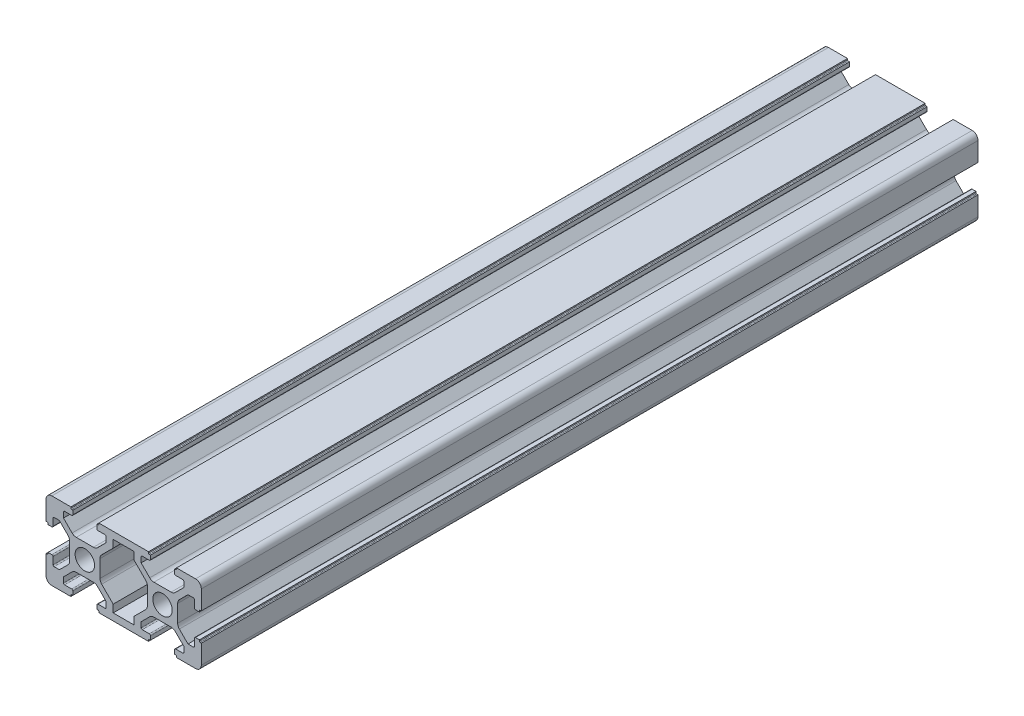
SolidWorks part; units mm, degrees
ref_plane "前视基准面" through (0, 0, 0) normal (0, 0, 1) x (1, 0, 0)
ref_plane "上视基准面" through (0, 0, 0) normal (0, 1, 0) x (1, 0, 0)
ref_plane "右视基准面" through (0, 0, 0) normal (1, 0, 0) x (0, 0, -1)
sketch "草图1" plane through (0, 0, 0) normal (0, 0, 1) x (1, 0, 0)
  line L0 (-1.9716, -6.6942) -> (-4.9322, -3.7335)
  line L1 (-5.3716, -2.6729) -> (-5.3716, 1.7645)
  line L2 (-4.9322, 2.8251) -> (-1.9716, 5.7858)
  line L3 (-0.7716, 9.5458) -> (-5.6716, 9.5458)
  line L4 (-5.6716, 9.5458) -> (-5.6716, 9.2458)
  line L5 (-5.8716, 9.0458) -> (-6.1716, 9.0458)
  line L6 (-6.1716, 9.0458) -> (-6.1716, 8.0458)
  line L7 (-5.8716, 7.7458) -> (-4.0716, 7.7458)
  line L8 (-3.7716, 7.4458) -> (-3.7716, 6.1058)
  line L9 (-3.7716, 6.1058) -> (-5.9922, 3.8851)
  line L10 (-7.0529, 3.4458) -> (-11.4903, 3.4458)
  line L11 (-12.5509, 3.8851) -> (-14.7716, 6.1058)
  line L12 (-14.7716, 6.1058) -> (-14.7716, 7.4458)
  line L13 (-14.4716, 7.7458) -> (-12.6716, 7.7458)
  line L14 (-12.3716, 8.0458) -> (-12.3716, 9.0458)
  line L15 (-12.3716, 9.0458) -> (-12.6716, 9.0458)
  line L16 (-12.8716, 9.2458) -> (-12.8716, 9.5458)
  line L17 (-12.8716, 9.5458) -> (-17.7716, 9.5458)
  line L18 (-19.2716, 8.0458) -> (-19.2716, 3.1458)
  line L19 (-19.2716, 3.1458) -> (-18.9716, 3.1458)
  line L20 (-18.7716, 2.9458) -> (-18.7716, 2.6458)
  line L21 (-18.7716, 2.6458) -> (-17.7716, 2.6458)
  line L22 (-17.4716, 2.9458) -> (-17.4716, 4.7458)
  line L23 (-17.1716, 5.0458) -> (-15.8316, 5.0458)
  line L24 (-15.8316, 5.0458) -> (-13.6109, 2.8251)
  line L25 (-13.1716, 1.7645) -> (-13.1716, -2.6729)
  line L26 (-13.6109, -3.7335) -> (-15.8316, -5.9542)
  line L27 (-15.8316, -5.9542) -> (-17.1716, -5.9542)
  line L28 (-17.4716, -5.6542) -> (-17.4716, -3.8542)
  line L29 (-17.7716, -3.5542) -> (-18.7716, -3.5542)
  line L30 (-18.7716, -3.5542) -> (-18.7716, -3.8542)
  line L31 (-18.9716, -4.0542) -> (-19.2716, -4.0542)
  line L32 (-19.2716, -4.0542) -> (-19.2716, -8.9542)
  line L33 (-17.7716, -10.4542) -> (-12.8716, -10.4542)
  line L34 (-12.8716, -10.4542) -> (-12.8716, -10.1542)
  line L35 (-12.6716, -9.9542) -> (-12.3716, -9.9542)
  line L36 (-12.3716, -9.9542) -> (-12.3716, -8.9542)
  line L37 (-12.6716, -8.6542) -> (-14.4716, -8.6542)
  line L38 (-14.7716, -8.3542) -> (-14.7716, -7.0142)
  line L39 (-14.7716, -7.0142) -> (-12.5509, -4.7935)
  line L40 (-11.4903, -4.3542) -> (-7.0529, -4.3542)
  line L41 (-5.9922, -4.7935) -> (-3.7716, -7.0142)
  line L42 (-3.7716, -7.0142) -> (-3.7716, -8.3542)
  line L43 (-4.0716, -8.6542) -> (-5.8716, -8.6542)
  line L44 (-6.1716, -8.9542) -> (-6.1716, -9.9542)
  line L45 (-6.1716, -9.9542) -> (-5.8716, -9.9542)
  line L46 (-5.6716, -10.1542) -> (-5.6716, -10.4542)
  line L47 (-5.6716, -10.4542) -> (-0.7716, -10.4542)
  line L48 (-0.7716, -10.4542) -> (7.1284, -10.4542)
  line L49 (7.1284, -10.4542) -> (7.1284, -10.1542)
  line L50 (7.3284, -9.9542) -> (7.6284, -9.9542)
  line L51 (7.6284, -9.9542) -> (7.6284, -8.9542)
  line L52 (7.3284, -8.6542) -> (5.5284, -8.6542)
  line L53 (5.2284, -8.3542) -> (5.2284, -7.0142)
  line L54 (5.2284, -7.0142) -> (7.4491, -4.7935)
  line L55 (8.5097, -4.3542) -> (12.9471, -4.3542)
  line L56 (14.0078, -4.7935) -> (16.2284, -7.0142)
  line L57 (16.2284, -7.0142) -> (16.2284, -8.3542)
  line L58 (15.9284, -8.6542) -> (14.1284, -8.6542)
  line L59 (13.8284, -8.9542) -> (13.8284, -9.9542)
  line L60 (13.8284, -9.9542) -> (14.1284, -9.9542)
  line L61 (14.3284, -10.1542) -> (14.3284, -10.4542)
  line L62 (14.3284, -10.4542) -> (19.2284, -10.4542)
  line L63 (20.7284, -8.9542) -> (20.7284, -4.0542)
  line L64 (20.7284, -4.0542) -> (20.4284, -4.0542)
  line L65 (20.2284, -3.8542) -> (20.2284, -3.5542)
  line L66 (20.2284, -3.5542) -> (19.2284, -3.5542)
  line L67 (18.9284, -3.8542) -> (18.9284, -5.6542)
  line L68 (18.6284, -5.9542) -> (17.2884, -5.9542)
  line L69 (17.2884, -5.9542) -> (15.0678, -3.7335)
  line L70 (14.6284, -2.6729) -> (14.6284, 1.7645)
  line L71 (15.0678, 2.8251) -> (17.2884, 5.0458)
  line L72 (17.2884, 5.0458) -> (18.6284, 5.0458)
  line L73 (18.9284, 4.7458) -> (18.9284, 2.9458)
  line L74 (19.2284, 2.6458) -> (20.2284, 2.6458)
  line L75 (20.2284, 2.6458) -> (20.2284, 2.9458)
  line L76 (20.4284, 3.1458) -> (20.7284, 3.1458)
  line L77 (20.7284, 3.1458) -> (20.7284, 8.0458)
  line L78 (19.2284, 9.5458) -> (14.3284, 9.5458)
  line L79 (14.3284, 9.5458) -> (14.3284, 9.2458)
  line L80 (14.1284, 9.0458) -> (13.8284, 9.0458)
  line L81 (13.8284, 9.0458) -> (13.8284, 8.0458)
  line L82 (14.1284, 7.7458) -> (15.9284, 7.7458)
  line L83 (16.2284, 7.4458) -> (16.2284, 6.1058)
  line L84 (16.2284, 6.1058) -> (14.0078, 3.8851)
  line L85 (12.9471, 3.4458) -> (8.5097, 3.4458)
  line L86 (7.4491, 3.8851) -> (5.2284, 6.1058)
  line L87 (5.2284, 6.1058) -> (5.2284, 7.4458)
  line L88 (5.5284, 7.7458) -> (7.3284, 7.7458)
  line L89 (7.6284, 8.0458) -> (7.6284, 9.0458)
  line L90 (7.6284, 9.0458) -> (7.3284, 9.0458)
  line L91 (7.1284, 9.2458) -> (7.1284, 9.5458)
  line L92 (7.1284, 9.5458) -> (2.2284, 9.5458)
  line L93 (3.4284, 5.7858) -> (6.3891, 2.8251)
  line L94 (6.8284, 1.7645) -> (6.8284, -2.6729)
  line L95 (6.3891, -3.7335) -> (3.4284, -6.6942)
  line L96 (-0.7716, 9.5458) -> (2.2284, 9.5458)
  line L99 (-1.9716, 7.7458) -> (3.4284, 7.7458)
  line L100 (3.4284, 7.7458) -> (3.4284, 5.7858)
  line L101 (-1.9716, 7.7458) -> (-1.9716, 5.7858)
  line L102 (-1.9716, -8.6542) -> (3.4284, -8.6542)
  line L103 (3.4284, -8.6542) -> (3.4284, -6.6942)
  line L104 (-1.9716, -8.6542) -> (-1.9716, -6.6942)
  arc A1 (-5.3716, -2.6729) -> (-4.9322, -3.7335) centre (-3.8716, -2.6729) ccw
  arc A2 (-4.9322, 2.8251) -> (-5.3716, 1.7645) centre (-3.8716, 1.7645) ccw
  arc A3 (-5.8716, 9.0458) -> (-5.6716, 9.2458) centre (-5.8716, 9.2458) ccw
  arc A4 (-6.1716, 8.0458) -> (-5.8716, 7.7458) centre (-5.8716, 8.0458) ccw
  arc A5 (-3.7716, 7.4458) -> (-4.0716, 7.7458) centre (-4.0716, 7.4458) ccw
  arc A6 (-7.0529, 3.4458) -> (-5.9922, 3.8851) centre (-7.0529, 4.9458) ccw
  arc A7 (-12.5509, 3.8851) -> (-11.4903, 3.4458) centre (-11.4903, 4.9458) ccw
  arc A8 (-14.4716, 7.7458) -> (-14.7716, 7.4458) centre (-14.4716, 7.4458) ccw
  arc A9 (-12.6716, 7.7458) -> (-12.3716, 8.0458) centre (-12.6716, 8.0458) ccw
  arc A10 (-12.8716, 9.2458) -> (-12.6716, 9.0458) centre (-12.6716, 9.2458) ccw
  arc A11 (-17.7716, 9.5458) -> (-19.2716, 8.0458) centre (-17.7716, 8.0458) ccw
  arc A12 (-18.7716, 2.9458) -> (-18.9716, 3.1458) centre (-18.9716, 2.9458) ccw
  arc A13 (-17.7716, 2.6458) -> (-17.4716, 2.9458) centre (-17.7716, 2.9458) ccw
  arc A14 (-17.1716, 5.0458) -> (-17.4716, 4.7458) centre (-17.1716, 4.7458) ccw
  arc A15 (-13.1716, 1.7645) -> (-13.6109, 2.8251) centre (-14.6716, 1.7645) ccw
  arc A16 (-13.6109, -3.7335) -> (-13.1716, -2.6729) centre (-14.6716, -2.6729) ccw
  arc A17 (-17.4716, -5.6542) -> (-17.1716, -5.9542) centre (-17.1716, -5.6542) ccw
  arc A18 (-17.4716, -3.8542) -> (-17.7716, -3.5542) centre (-17.7716, -3.8542) ccw
  arc A19 (-18.9716, -4.0542) -> (-18.7716, -3.8542) centre (-18.9716, -3.8542) ccw
  arc A20 (-19.2716, -8.9542) -> (-17.7716, -10.4542) centre (-17.7716, -8.9542) ccw
  arc A21 (-12.6716, -9.9542) -> (-12.8716, -10.1542) centre (-12.6716, -10.1542) ccw
  arc A22 (-12.3716, -8.9542) -> (-12.6716, -8.6542) centre (-12.6716, -8.9542) ccw
  arc A23 (-14.7716, -8.3542) -> (-14.4716, -8.6542) centre (-14.4716, -8.3542) ccw
  arc A24 (-11.4903, -4.3542) -> (-12.5509, -4.7935) centre (-11.4903, -5.8542) ccw
  arc A25 (-5.9922, -4.7935) -> (-7.0529, -4.3542) centre (-7.0529, -5.8542) ccw
  arc A26 (-4.0716, -8.6542) -> (-3.7716, -8.3542) centre (-4.0716, -8.3542) ccw
  arc A27 (-5.8716, -8.6542) -> (-6.1716, -8.9542) centre (-5.8716, -8.9542) ccw
  arc A28 (-5.6716, -10.1542) -> (-5.8716, -9.9542) centre (-5.8716, -10.1542) ccw
  arc A29 (7.3284, -9.9542) -> (7.1284, -10.1542) centre (7.3284, -10.1542) ccw
  arc A30 (7.6284, -8.9542) -> (7.3284, -8.6542) centre (7.3284, -8.9542) ccw
  arc A31 (5.2284, -8.3542) -> (5.5284, -8.6542) centre (5.5284, -8.3542) ccw
  arc A32 (8.5097, -4.3542) -> (7.4491, -4.7935) centre (8.5097, -5.8542) ccw
  arc A33 (14.0078, -4.7935) -> (12.9471, -4.3542) centre (12.9471, -5.8542) ccw
  arc A34 (15.9284, -8.6542) -> (16.2284, -8.3542) centre (15.9284, -8.3542) ccw
  arc A35 (14.1284, -8.6542) -> (13.8284, -8.9542) centre (14.1284, -8.9542) ccw
  arc A36 (14.3284, -10.1542) -> (14.1284, -9.9542) centre (14.1284, -10.1542) ccw
  arc A37 (19.2284, -10.4542) -> (20.7284, -8.9542) centre (19.2284, -8.9542) ccw
  arc A38 (20.2284, -3.8542) -> (20.4284, -4.0542) centre (20.4284, -3.8542) ccw
  arc A39 (19.2284, -3.5542) -> (18.9284, -3.8542) centre (19.2284, -3.8542) ccw
  arc A40 (18.6284, -5.9542) -> (18.9284, -5.6542) centre (18.6284, -5.6542) ccw
  arc A41 (14.6284, -2.6729) -> (15.0678, -3.7335) centre (16.1284, -2.6729) ccw
  arc A42 (15.0678, 2.8251) -> (14.6284, 1.7645) centre (16.1284, 1.7645) ccw
  arc A43 (18.9284, 4.7458) -> (18.6284, 5.0458) centre (18.6284, 4.7458) ccw
  arc A44 (18.9284, 2.9458) -> (19.2284, 2.6458) centre (19.2284, 2.9458) ccw
  arc A45 (20.4284, 3.1458) -> (20.2284, 2.9458) centre (20.4284, 2.9458) ccw
  arc A46 (20.7284, 8.0458) -> (19.2284, 9.5458) centre (19.2284, 8.0458) ccw
  arc A47 (14.1284, 9.0458) -> (14.3284, 9.2458) centre (14.1284, 9.2458) ccw
  arc A48 (13.8284, 8.0458) -> (14.1284, 7.7458) centre (14.1284, 8.0458) ccw
  arc A49 (16.2284, 7.4458) -> (15.9284, 7.7458) centre (15.9284, 7.4458) ccw
  arc A50 (12.9471, 3.4458) -> (14.0078, 3.8851) centre (12.9471, 4.9458) ccw
  arc A51 (7.4491, 3.8851) -> (8.5097, 3.4458) centre (8.5097, 4.9458) ccw
  arc A52 (5.5284, 7.7458) -> (5.2284, 7.4458) centre (5.5284, 7.4458) ccw
  arc A53 (7.3284, 7.7458) -> (7.6284, 8.0458) centre (7.3284, 8.0458) ccw
  arc A54 (7.1284, 9.2458) -> (7.3284, 9.0458) centre (7.3284, 9.2458) ccw
  arc A55 (6.8284, 1.7645) -> (6.3891, 2.8251) centre (5.3284, 1.7645) ccw
  arc A56 (6.3891, -3.7335) -> (6.8284, -2.6729) centre (5.3284, -2.6729) ccw
  circle A58 centre (10.7284, -0.4542) radius 2.5
  circle A63 centre (-9.2716, -0.4542) radius 2.5
extrude "凸台-拉伸1" add sketch "草图1" along normal blind 200
